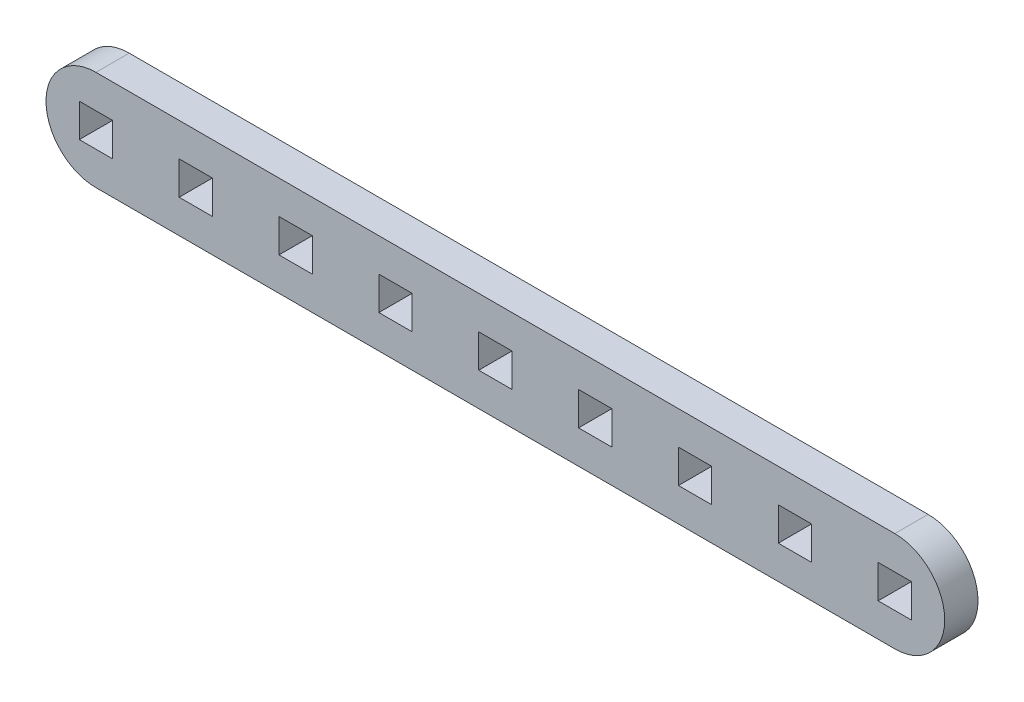
SolidWorks part; units mm, degrees
ref_plane "Alzado" through (0, 0, 0) normal (0, 0, 1) x (1, 0, 0)
ref_plane "Planta" through (0, 0, 0) normal (0, 1, 0) x (1, 0, 0)
ref_plane "Vista lateral" through (0, 0, 0) normal (1, 0, 0) x (0, 0, -1)
sketch "Model" plane through (0, 0, 0) normal (0, 0, 1) x (1, 0, 0)
  line L0 (10.1979, 296.3366) -> (10.1979, 293.3366)
  line L1 (13.1979, 296.3366) -> (10.1979, 296.3366)
  line L2 (13.1979, 293.3366) -> (13.1979, 296.3366)
  line L3 (10.1979, 293.3366) -> (13.1979, 293.3366)
  line L4 (19.1979, 296.3366) -> (19.1979, 293.3366)
  line L5 (22.1979, 296.3366) -> (19.1979, 296.3366)
  line L6 (22.1979, 293.3366) -> (22.1979, 296.3366)
  line L7 (19.1979, 293.3366) -> (22.1979, 293.3366)
  line L8 (28.1979, 296.3366) -> (28.1979, 293.3366)
  line L9 (31.1979, 296.3366) -> (28.1979, 296.3366)
  line L10 (31.1979, 293.3366) -> (31.1979, 296.3366)
  line L11 (28.1979, 293.3366) -> (31.1979, 293.3366)
  line L12 (37.1979, 296.3366) -> (37.1979, 293.3366)
  line L13 (40.1979, 296.3366) -> (37.1979, 296.3366)
  line L14 (40.1979, 293.3366) -> (40.1979, 296.3366)
  line L15 (37.1979, 293.3366) -> (40.1979, 293.3366)
  line L16 (46.1979, 296.3366) -> (46.1979, 293.3366)
  line L17 (49.1979, 296.3366) -> (46.1979, 296.3366)
  line L18 (49.1979, 293.3366) -> (49.1979, 296.3366)
  line L19 (46.1979, 293.3366) -> (49.1979, 293.3366)
  line L20 (55.1979, 296.3366) -> (55.1979, 293.3366)
  line L21 (58.1979, 296.3366) -> (55.1979, 296.3366)
  line L22 (58.1979, 293.3366) -> (58.1979, 296.3366)
  line L23 (55.1979, 293.3366) -> (58.1979, 293.3366)
  line L24 (64.1979, 296.3366) -> (64.1979, 293.3366)
  line L25 (67.1979, 296.3366) -> (64.1979, 296.3366)
  line L26 (67.1979, 293.3366) -> (67.1979, 296.3366)
  line L27 (64.1979, 293.3366) -> (67.1979, 293.3366)
  line L28 (73.1979, 296.3366) -> (73.1979, 293.3366)
  line L29 (76.1979, 296.3366) -> (73.1979, 296.3366)
  line L30 (76.1979, 293.3366) -> (76.1979, 296.3366)
  line L31 (73.1979, 293.3366) -> (76.1979, 293.3366)
  line L32 (82.1979, 296.3366) -> (82.1979, 293.3366)
  line L33 (85.1979, 296.3366) -> (82.1979, 296.3366)
  line L34 (85.1979, 293.3366) -> (85.1979, 296.3366)
  line L35 (82.1979, 293.3366) -> (85.1979, 293.3366)
  line L36 (11.6979, 299.3366) -> (83.6979, 299.3366)
  line L37 (11.6979, 290.3366) -> (83.6979, 290.3366)
  arc A0 (83.6979, 290.3366) -> (83.6979, 299.3366) centre (83.6979, 294.8366) ccw
  arc A1 (11.6979, 299.3366) -> (11.6979, 290.3366) centre (11.6979, 294.8366) ccw
extrude "Saliente-Extruir1" add sketch "Model" along normal blind 3
